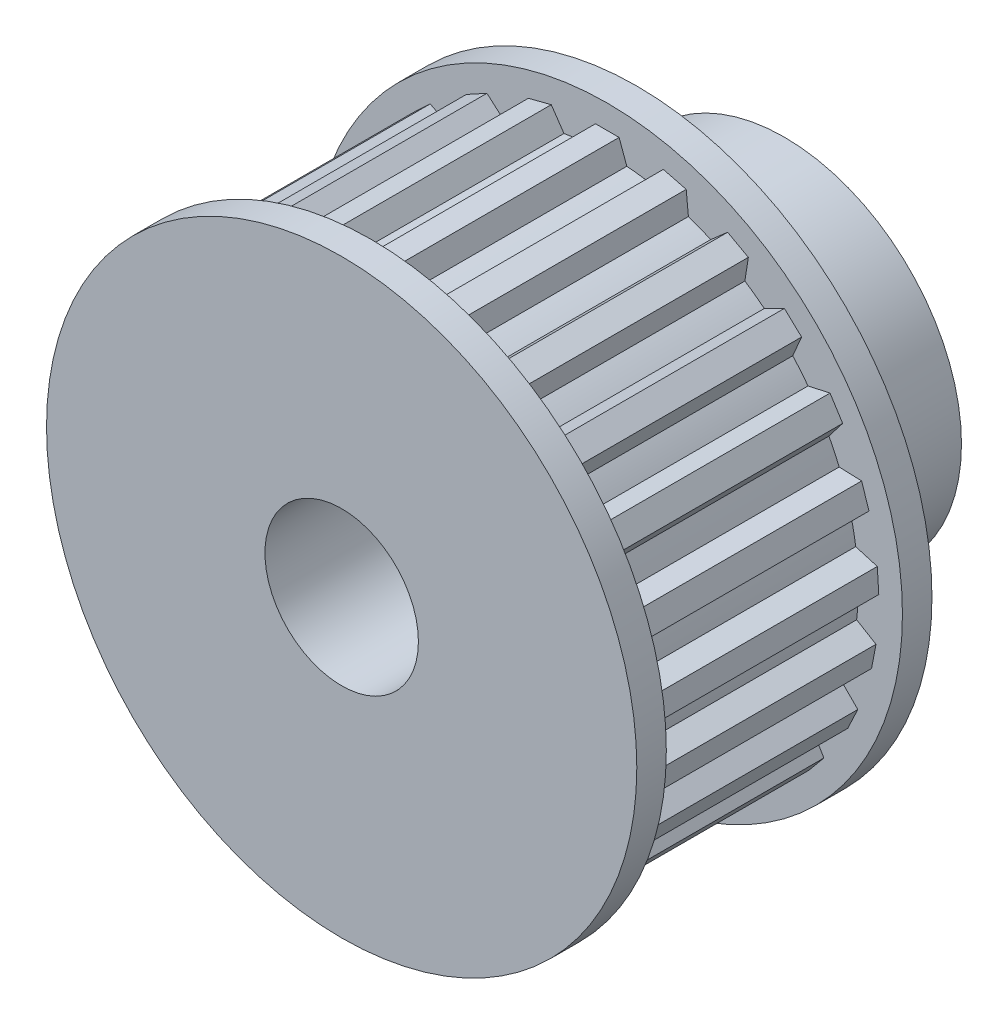
SolidWorks part; units mm, degrees
ref_plane "Front Plane" through (0, 0, 0) normal (0, 0, 1) x (1, 0, 0)
ref_plane "Top Plane" through (0, 0, 0) normal (0, 1, 0) x (1, 0, 0)
ref_plane "Right Plane" through (0, 0, 0) normal (1, 0, 0) x (0, 0, -1)
sketch "Sketch1" plane through (0, 0, 0) normal (0, 0, 1) x (1, 0, 0)
  line L0 (-0.4, 9.1913) -> (-0.661, 8.4743)
  line L1 (-0.4, 9.1913) -> (0.4, 9.1913)
  line L2 (0.4, 9.1913) -> (0.661, 8.4743)
  line L3 (0, 9.2) -> (0, -9.2) construction
  line L4 (1.8984, 9.002) -> (1.4672, 8.3724)
  line L5 (1.8984, 9.002) -> (2.6732, 8.8031)
  line L6 (2.6732, 8.8031) -> (2.7477, 8.0436)
  line L7 (4.0774, 8.2471) -> (3.5033, 7.7445)
  line L8 (4.0774, 8.2471) -> (4.7785, 7.8617)
  line L9 (4.7785, 7.8617) -> (4.6617, 7.1076)
  line L10 (6.0003, 6.974) -> (5.3192, 6.6299)
  line L11 (6.0003, 6.974) -> (6.5835, 6.4264)
  line L12 (6.5835, 6.4264) -> (6.2829, 5.725)
  line L13 (7.5461, 5.2627) -> (6.8009, 5.0988)
  line L14 (7.5461, 5.2627) -> (7.9748, 4.5872)
  line L15 (7.9748, 4.5872) -> (7.5092, 3.9827)
  line L16 (8.6178, 3.2207) -> (7.8552, 3.2473)
  line L17 (8.6178, 3.2207) -> (8.8651, 2.4598)
  line L18 (8.8651, 2.4598) -> (8.2638, 1.9901)
  line L19 (9.148, 0.9763) -> (8.416, 1.1918)
  line L20 (9.148, 0.9763) -> (9.1983, 0.1779)
  line L21 (9.1983, 0.1779) -> (8.499, -0.1276)
  line L22 (9.1034, -1.3294) -> (8.448, -0.9386)
  line L23 (9.1034, -1.3294) -> (8.9535, -2.1152)
  line L24 (8.9535, -2.1152) -> (8.2003, -2.2372)
  line L25 (8.4868, -3.5515) -> (7.9492, -3.0101)
  line L26 (8.4868, -3.5515) -> (8.1462, -4.2754)
  line L27 (8.1462, -4.2754) -> (7.3863, -4.2062)
  line L28 (7.337, -5.5505) -> (6.9509, -4.8924)
  line L29 (7.337, -5.5505) -> (6.827, -6.167)
  line L30 (6.827, -6.167) -> (6.1082, -5.911)
  line L31 (5.7261, -7.2008) -> (5.5158, -6.4673)
  line L32 (5.7261, -7.2008) -> (5.0789, -7.671)
  line L33 (5.0789, -7.671) -> (4.4463, -7.2443)
  line L34 (3.7555, -8.3986) -> (3.7341, -7.6358)
  line L35 (3.7555, -8.3986) -> (3.0116, -8.6931)
  line L36 (3.0116, -8.6931) -> (2.505, -8.1225)
  line L37 (1.5488, -9.0687) -> (1.7179, -8.3246)
  line L38 (1.5488, -9.0687) -> (0.7551, -9.169)
  line L39 (0.7551, -9.169) -> (0.4063, -8.4903)
  line L40 (-0.7551, -9.169) -> (-0.4063, -8.4903)
  line L41 (-0.7551, -9.169) -> (-1.5488, -9.0687)
  line L42 (-1.5488, -9.0687) -> (-1.7179, -8.3246)
  line L43 (-3.0116, -8.6931) -> (-2.505, -8.1225)
  line L44 (-3.0116, -8.6931) -> (-3.7555, -8.3986)
  line L45 (-3.7555, -8.3986) -> (-3.7341, -7.6358)
  line L46 (-5.0789, -7.671) -> (-4.4463, -7.2443)
  line L47 (-5.0789, -7.671) -> (-5.7261, -7.2008)
  line L48 (-5.7261, -7.2008) -> (-5.5158, -6.4673)
  line L49 (-6.827, -6.167) -> (-6.1082, -5.911)
  line L50 (-6.827, -6.167) -> (-7.337, -5.5505)
  line L51 (-7.337, -5.5505) -> (-6.9509, -4.8924)
  line L52 (-8.1462, -4.2754) -> (-7.3863, -4.2062)
  line L53 (-8.1462, -4.2754) -> (-8.4868, -3.5515)
  line L54 (-8.4868, -3.5515) -> (-7.9492, -3.0101)
  line L55 (-8.9535, -2.1152) -> (-8.2003, -2.2372)
  line L56 (-8.9535, -2.1152) -> (-9.1034, -1.3294)
  line L57 (-9.1034, -1.3294) -> (-8.448, -0.9386)
  line L58 (-9.1983, 0.1779) -> (-8.499, -0.1276)
  line L59 (-9.1983, 0.1779) -> (-9.148, 0.9763)
  line L60 (-9.148, 0.9763) -> (-8.416, 1.1918)
  line L61 (-8.8651, 2.4598) -> (-8.2638, 1.9901)
  line L62 (-8.8651, 2.4598) -> (-8.6178, 3.2207)
  line L63 (-8.6178, 3.2207) -> (-7.8552, 3.2473)
  line L64 (-7.9748, 4.5872) -> (-7.5092, 3.9827)
  line L65 (-7.9748, 4.5872) -> (-7.5461, 5.2627)
  line L66 (-7.5461, 5.2627) -> (-6.8009, 5.0988)
  line L67 (-6.5835, 6.4264) -> (-6.2829, 5.725)
  line L68 (-6.5835, 6.4264) -> (-6.0003, 6.974)
  line L69 (-6.0003, 6.974) -> (-5.3192, 6.6299)
  line L70 (-4.7785, 7.8617) -> (-4.6617, 7.1076)
  line L71 (-4.7785, 7.8617) -> (-4.0774, 8.2471)
  line L72 (-4.0774, 8.2471) -> (-3.5033, 7.7445)
  line L73 (-2.6732, 8.8031) -> (-2.7477, 8.0436)
  line L74 (-2.6732, 8.8031) -> (-1.8984, 9.002)
  line L75 (-1.8984, 9.002) -> (-1.4672, 8.3724)
  arc A0 (1.4672, 8.3724) -> (0.661, 8.4743) centre (0, 0) ccw
  arc A2 (3.5033, 7.7445) -> (2.7477, 8.0436) centre (0, 0) ccw
  arc A3 (5.3192, 6.6299) -> (4.6617, 7.1076) centre (0, 0) ccw
  arc A4 (6.8009, 5.0988) -> (6.2829, 5.725) centre (0, 0) ccw
  arc A5 (7.8552, 3.2473) -> (7.5092, 3.9827) centre (0, 0) ccw
  arc A6 (8.416, 1.1918) -> (8.2638, 1.9901) centre (0, 0) ccw
  arc A7 (8.448, -0.9386) -> (8.499, -0.1276) centre (0, 0) ccw
  arc A8 (7.9492, -3.0101) -> (8.2003, -2.2372) centre (0, 0) ccw
  arc A9 (6.9509, -4.8924) -> (7.3863, -4.2062) centre (0, 0) ccw
  arc A10 (5.5158, -6.4673) -> (6.1082, -5.911) centre (0, 0) ccw
  arc A11 (3.7341, -7.6358) -> (4.4463, -7.2443) centre (0, 0) ccw
  arc A12 (1.7179, -8.3246) -> (2.505, -8.1225) centre (0, 0) ccw
  arc A13 (-0.4063, -8.4903) -> (0.4063, -8.4903) centre (0, 0) ccw
  arc A14 (-2.505, -8.1225) -> (-1.7179, -8.3246) centre (0, 0) ccw
  arc A15 (-4.4463, -7.2443) -> (-3.7341, -7.6358) centre (0, 0) ccw
  arc A16 (-6.1082, -5.911) -> (-5.5158, -6.4673) centre (0, 0) ccw
  arc A17 (-7.3863, -4.2062) -> (-6.9509, -4.8924) centre (0, 0) ccw
  arc A18 (-8.2003, -2.2372) -> (-7.9492, -3.0101) centre (0, 0) ccw
  arc A19 (-8.499, -0.1276) -> (-8.448, -0.9386) centre (0, 0) ccw
  arc A20 (-8.2638, 1.9901) -> (-8.416, 1.1918) centre (0, 0) ccw
  arc A21 (-7.5092, 3.9827) -> (-7.8552, 3.2473) centre (0, 0) ccw
  arc A22 (-6.2829, 5.725) -> (-6.8009, 5.0988) centre (0, 0) ccw
  arc A23 (-4.6617, 7.1076) -> (-5.3192, 6.6299) centre (0, 0) ccw
  arc A24 (-2.7477, 8.0436) -> (-3.5033, 7.7445) centre (0, 0) ccw
  arc A25 (-0.661, 8.4743) -> (-1.4672, 8.3724) centre (0, 0) ccw
  point P109 (0, 0)
  dimension "D1" = 17
  dimension "D3" = 0.8
  dimension "D4" = 40
  dimension "D5" = 25
extrude "Boss-Extrude1" add sketch "Sketch1" along normal mid plane 10
sketch "Sketch2" plane through (0, 0, 5) normal (0, 0, 1) x (1, 0, 0)
  circle A0 centre (0, 0) radius 10
  dimension "D1" = 20
extrude "Boss-Extrude2" add sketch "Sketch2" against normal blind 1
mirror "Mirror1" about plane through (0, 0, 0) normal (0, 0, 1) of "Boss-Extrude2"
sketch "Sketch4" plane through (0, 0, -5) normal (0, 0, -1) x (-1, 0, 0)
  circle A0 centre (0, 0) radius 6
  dimension "D1" = 12
extrude "Boss-Extrude3" add sketch "Sketch4" along normal blind 5
sketch "Sketch5" plane through (0, 0, 5) normal (0, 0, 1) x (1, 0, 0)
  circle A0 centre (0, 0) radius 2.6
  dimension "D1" = 5.2
extrude "Cut-Extrude1" cut sketch "Sketch5" against normal up to next
equation "\"d1\"= 16"
